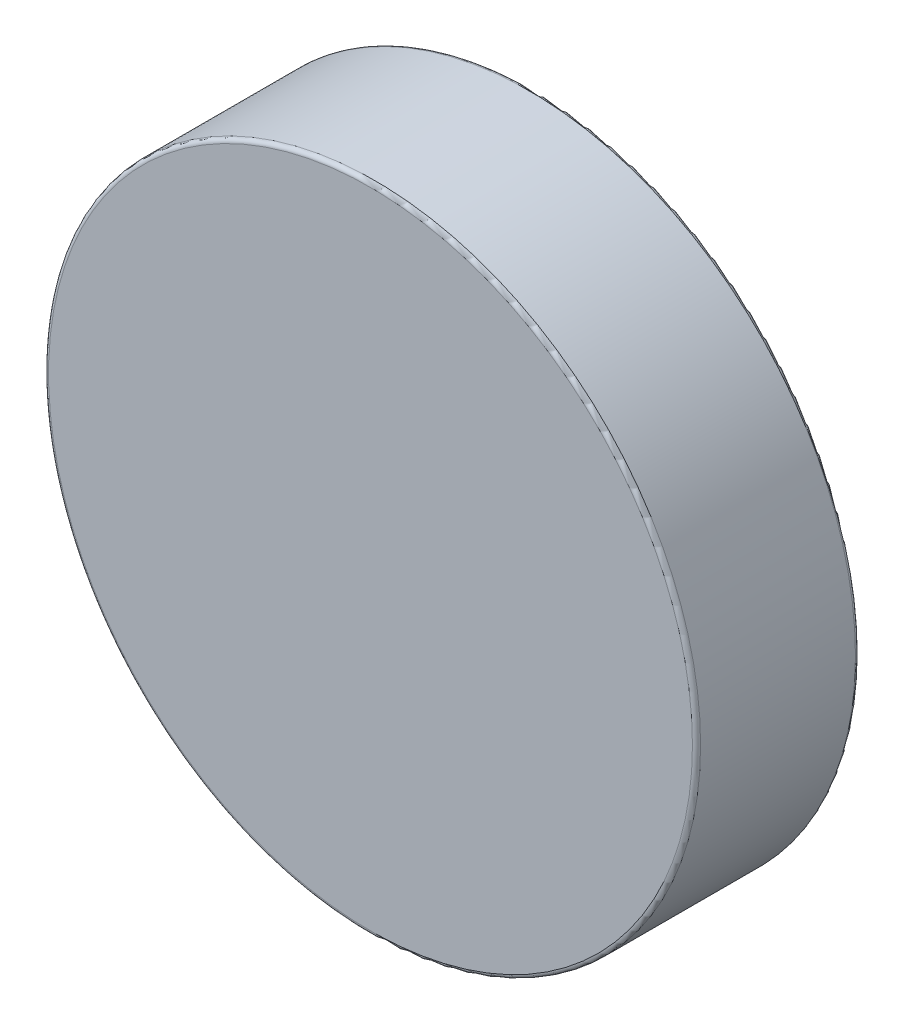
SolidWorks part; units mm, degrees
ref_plane "Front Plane" through (0, 0, 0) normal (0, 0, 1) x (1, 0, 0)
ref_plane "Top Plane" through (0, 0, 0) normal (0, 1, 0) x (1, 0, 0)
ref_plane "Right Plane" through (0, 0, 0) normal (1, 0, 0) x (0, 0, -1)
sketch "Sketch1" plane through (0, 0, 0) normal (0, 0, 1) x (1, 0, 0)
  circle A0 centre (0, 0) radius 3.175 construction
  dimension "OD" = 6.35
sketch "Sketch2" plane through (0, 0, 0) normal (1, 0, 0) x (0, 0, -1)
  line L0 (-0.7937, 0) -> (0.7938, 0) construction
  line L1 (0, 3.175) -> (0, -3.175) construction
  line L3 (-0.7938, 3.175) -> (0.7937, 3.175)
  line L4 (-0.7938, 3.175) -> (-0.7938, -3.175)
  line L5 (-0.7938, -3.175) -> (0.7937, -3.175)
  line L6 (0.7937, 3.175) -> (0.7937, -3.175)
  point P4 (0, 0)
  point P12 (0, 3.175)
  dimension "Thickness" = 1.5875
sketch "Sketch3" plane through (0, 0, 0) normal (0, 0, 1) x (1, 0, 0)
  circle A0 centre (0, 0) radius 3.175 construction
  circle A1 centre (0, 0) radius 3.175
extrude "Boss-Extrude1" add sketch "Sketch3" along normal up to vertex (0.7937 mm away) and the other way up to vertex (0.7937 mm away) up to point (0, 3.175, 0.7938) other way up to point (0, 3.175, -0.7937)
fillet "Fillet1" radius 0.0397 2 edges at (3.175, 0, -0.7937) (3.175, 0, 0.7938)
equation "\"Fillet@Fillet1\"=\"Thickness@Sketch2\"*.025"
